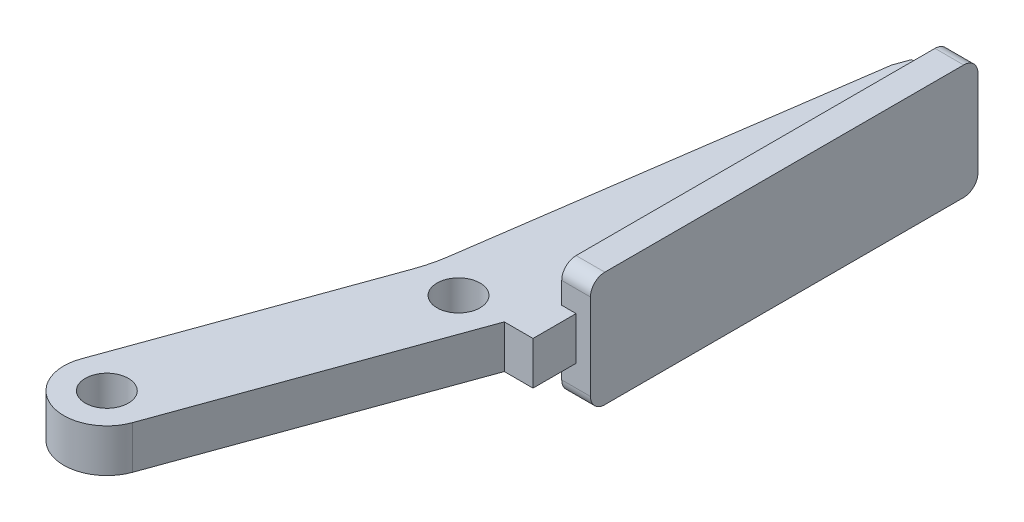
SolidWorks part; units mm, degrees
ref_plane "Front Plane" through (0, 0, 0) normal (0, 0, 1) x (1, 0, 0)
ref_plane "Top Plane" through (0, 0, 0) normal (0, 1, 0) x (1, 0, 0)
ref_plane "Right Plane" through (0, 0, 0) normal (1, 0, 0) x (0, 0, -1)
sketch "Sketch1" plane through (0, 0, 0) normal (0, 1, 0) x (1, 0, 0)
  line L0 (-2.8217, 1.0189) -> (3.3104, 18)
  line L2 (7.6896, 47) -> (8.0507, 48)
  line L3 (8.0507, 48) -> (11.6896, 48)
  line L4 (11.6896, 48) -> (11.6896, 18)
  line L5 (11.6896, 18) -> (9.6896, 18)
  line L6 (9.6896, 18) -> (2.8217, -1.0189)
  line L7 (0, 0) -> (6.5, 18) construction
  line L8 (3.803, 19.973) -> (7.6896, 47)
  arc A0 (-2.8217, 1.0189) -> (2.8217, -1.0189) centre (0, 0) ccw
  circle A2 centre (6.5, 18) radius 1.5
  arc A3 (3.3104, 18) -> (3.803, 19.973) centre (-6.0951, 21.3964) ccw
  circle A4 centre (0, 0) radius 1.5
  point P17 (10.6896, 18)
  dimension "D1" = 3
  dimension "D7" = 6.5
  dimension "D8" = 3
  dimension "D9" = 10
  dimension "D2" = 2
  dimension "D3" = 30
  dimension "D4" = 4
  dimension "D5" = 1
  dimension "D6" = 18
extrude "Boss-Extrude1" add sketch "Sketch1" along normal mid plane 3
sketch "Sketch3" plane through (0, 0, 0) normal (0, 1, 0) x (1, 0, 0)
  line L0 (11.6896, 48) -> (11.6896, 18) construction
  line L1 (10.6896, 21) -> (12.6896, 21)
  line L2 (10.6896, 21) -> (10.6896, 48)
  line L3 (10.6896, 48) -> (12.6896, 48)
  line L4 (12.6896, 21) -> (12.6896, 48)
  line L5 (10.6896, 21) -> (12.6896, 48) construction
  line L6 (10.6896, 48) -> (12.6896, 21) construction
  line L7 (8.0507, 48) -> (11.6896, 48) construction
  point P0 (11.6896, 34.5)
  point P7 (10.6896, 48)
  dimension "D1" = 2
  dimension "D2" = 27
extrude "Boss-Extrude2" add sketch "Sketch3" along normal mid plane 8
fillet "Fillet1" radius 1 4 edges at (11.6896, -4, -48) (11.6896, 4, -48) (11.6896, -4, -21) (11.6896, 4, -21)
